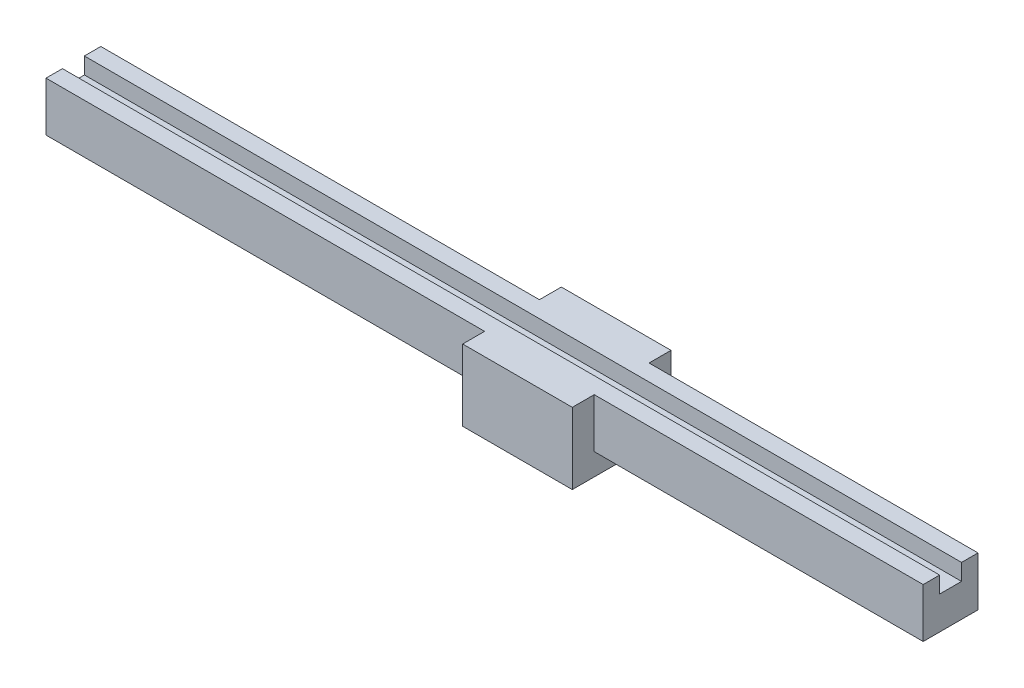
SolidWorks part; units mm, degrees
ref_plane "Front Plane" through (0, 0, 0) normal (0, 0, 1) x (1, 0, 0)
ref_plane "Top Plane" through (0, 0, 0) normal (0, 1, 0) x (1, 0, 0)
ref_plane "Right Plane" through (0, 0, 0) normal (1, 0, 0) x (0, 0, -1)
sketch "Sketch6" plane through (0, 0, 0) normal (1, 0, 0) x (0, 0, -1)
  line L1 (-1.25, -1.125) -> (1.25, -1.125)
  line L2 (-1.25, -1.125) -> (-1.25, 1.125)
  line L3 (-1.25, 1.125) -> (1.25, 1.125)
  line L4 (1.25, -1.125) -> (1.25, 1.125)
  line L5 (-1.25, -1.125) -> (1.25, 1.125) construction
  line L6 (-1.25, 1.125) -> (1.25, -1.125) construction
  point P0 (0, 0)
  dimension "D1" = 2.25
  dimension "D2" = 2.5
extrude "Boss-Extrude1" add sketch "Sketch6" along normal mid plane 40
sketch "Sketch7" plane through (0, 0, 0) normal (1, 0, 0) x (0, 0, -1)
  line L0 (0, 1.125) -> (0, -1.125) construction
  line L1 (1.25, 1.125) -> (-1.25, 1.125) construction
  line L2 (-1.25, -1.125) -> (1.25, -1.125) construction
  line L3 (0.5, 1.125) -> (-0.5, 1.125)
  line L4 (-0.5, 1.125) -> (-0.5, 0.375)
  line L5 (-0.5, 0.375) -> (0.5, 0.375)
  line L6 (0.5, 1.125) -> (0.5, 0.375)
  point P10 (0, 0.375)
  dimension "D1" = 1
  dimension "D2" = 0.75
extrude "Cut-Extrude1" cut sketch "Sketch7" against normal through all both and the other way through all
sketch "Sketch8" plane through (0, 0, 0) normal (1, 0, 0) x (0, 0, -1)
  line L3 (-2.25, 1.125) -> (-1.25, 1.125)
  line L4 (-1.25, 1.125) -> (-1.25, -1.125)
  line L5 (-1.25, -1.125) -> (1.25, -1.125)
  line L6 (-2.25, -2.125) -> (2.25, -2.125)
  line L7 (2.25, -2.125) -> (2.25, 1.125)
  line L8 (-2.25, 1.125) -> (-2.25, -2.125)
  line L9 (-2.25, -2.125) -> (2.25, -2.125)
  line L10 (2.25, -2.125) -> (2.25, 1.125)
  line L11 (-2.25, 1.125) -> (-2.25, -2.125)
  line L12 (1.25, -1.125) -> (1.25, 1.125)
  line L13 (1.25, 1.125) -> (2.25, 1.125)
  line L14 (1.25, -1.125) -> (1.25, 1.125) construction
  point P0 (1.25, 1.25)
  dimension "D1" = 1
extrude "Boss-Extrude2" add sketch "Sketch8" along normal blind 5
